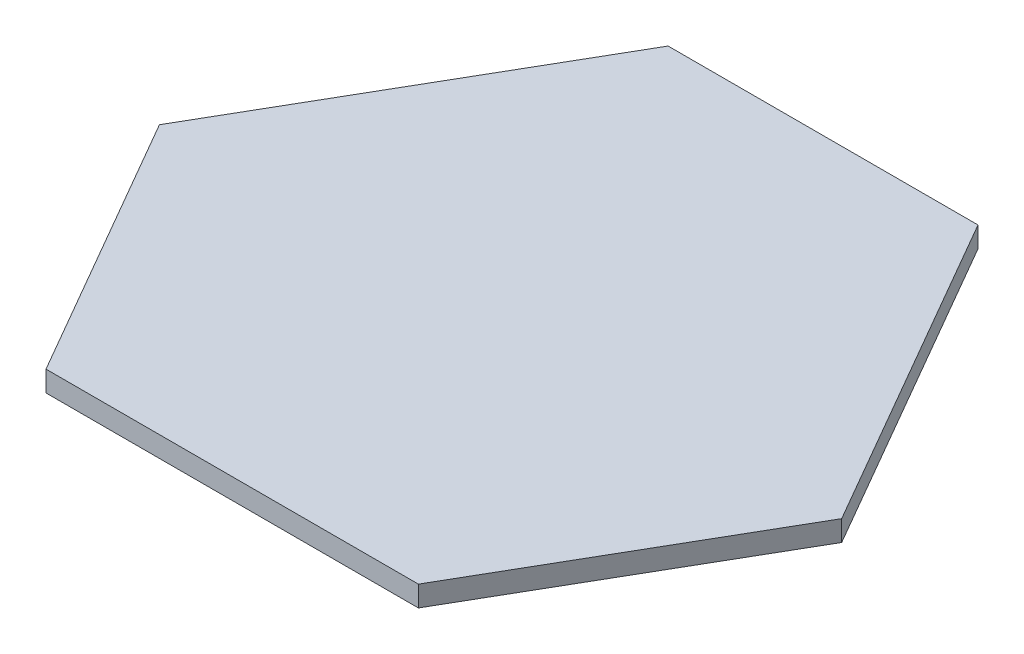
SolidWorks part; units mm, degrees
ref_plane "前基準面" through (0, 0, 0) normal (0, 0, 1) x (1, 0, 0)
ref_plane "上基準面" through (0, 0, 0) normal (0, 1, 0) x (1, 0, 0)
ref_plane "右基準面" through (0, 0, 0) normal (1, 0, 0) x (0, 0, -1)
sketch "草圖1" plane through (0, 0, 0) normal (0, 1, 0) x (1, 0, 0)
  line L0 (-90.1222, 0) -> (90.1222, 0)
  line L1 (90.1222, 0) -> (165.1222, 129.9038)
  line L2 (165.1222, 129.9038) -> (75, 286)
  line L3 (75, 286) -> (-75, 286)
  line L4 (-75, 286) -> (-165.1222, 129.9038)
  line L5 (-165.1222, 129.9038) -> (-90.1222, 0)
  dimension "D1" = 286
  dimension "D2" = 286
  dimension "D3" = 286
  dimension "D4" = 150
  dimension "D5" = 60
extrude "填料-伸長1" add sketch "草圖1" along normal blind 10
